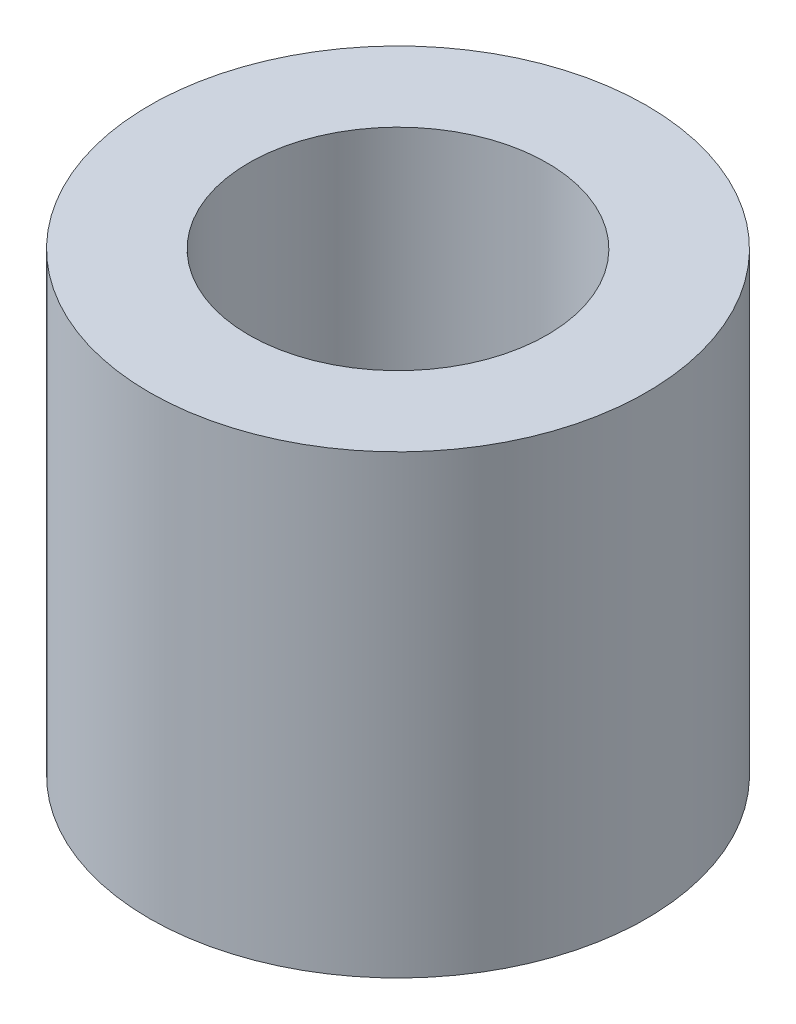
SolidWorks part; units mm, degrees
ref_plane "Front Plane" through (0, 0, 0) normal (0, 0, 1) x (1, 0, 0)
ref_plane "Top Plane" through (0, 0, 0) normal (0, 1, 0) x (1, 0, 0)
ref_plane "Right Plane" through (0, 0, 0) normal (1, 0, 0) x (0, 0, -1)
sketch "Sketch1" plane through (0, 0, 0) normal (0, 1, 0) x (1, 0, 0)
  circle A0 centre (0, 0) radius 3
  circle A1 centre (0, 0) radius 1.8
  dimension "D1" = 6
  dimension "D2" = 3.6
extrude "Boss-Extrude1" add sketch "Sketch1" along normal blind 5.5
